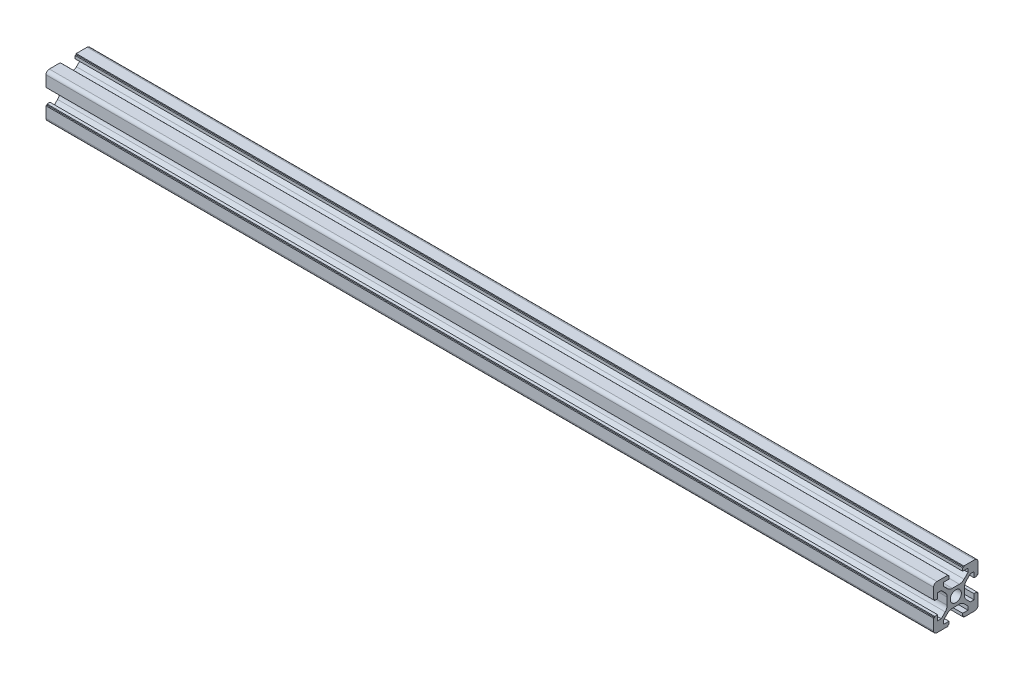
SolidWorks part; units mm, degrees
ref_plane "前视基准面" through (0, 0, 0) normal (0, 0, 1) x (1, 0, 0)
ref_plane "上视基准面" through (0, 0, 0) normal (0, 1, 0) x (1, 0, 0)
ref_plane "右视基准面" through (0, 0, 0) normal (1, 0, 0) x (0, 0, -1)
sketch "草图1" plane through (0, 0, 0) normal (1, 0, 0) x (0, 0, -1)
  line L0 (0, 0) -> (-10, 0) construction
  line L1 (0, 0) -> (0, 10) construction
  line L2 (0, 0) -> (-10, 10) construction
  line L3 (-10, 10) -> (-10, 3.6)
  line L4 (-10, 3.6) -> (-9.531, 3.6)
  line L5 (-9.531, 3.6) -> (-9.531, 3.1)
  line L6 (-9.531, 3.1) -> (-8.2, 3.1)
  line L7 (-8.2, 3.1) -> (-8.2, 5.5)
  line L8 (-8.2, 5.5) -> (-6.5607, 5.5)
  line L9 (-6.5607, 5.5) -> (-3.9, 2.8393)
  line L10 (-3.9, 2.8393) -> (-3.9, 0)
  line L11 (-3.6, 9.531) -> (-3.1, 9.531)
  line L12 (-2.8393, 3.9) -> (0, 3.9)
  line L13 (-5.5, 6.5607) -> (-2.8393, 3.9)
  line L14 (-5.5, 8.2) -> (-5.5, 6.5607)
  line L15 (-3.1, 8.2) -> (-5.5, 8.2)
  line L16 (-3.1, 9.531) -> (-3.1, 8.2)
  line L17 (-3.6, 10) -> (-3.6, 9.531)
  line L18 (-10, 10) -> (-3.6, 10)
  line L19 (0, 0) -> (0, 10) construction
  line L20 (0, 0) -> (10, 0) construction
  line L21 (0, 0) -> (10, 10) construction
  line L22 (10, 10) -> (3.6, 10)
  line L23 (3.6, 10) -> (3.6, 9.531)
  line L24 (3.6, 9.531) -> (3.1, 9.531)
  line L25 (3.1, 9.531) -> (3.1, 8.2)
  line L26 (3.1, 8.2) -> (5.5, 8.2)
  line L27 (5.5, 8.2) -> (5.5, 6.5607)
  line L28 (5.5, 6.5607) -> (2.8393, 3.9)
  line L29 (2.8393, 3.9) -> (0, 3.9)
  line L30 (9.531, 3.6) -> (9.531, 3.1)
  line L31 (3.9, 2.8393) -> (3.9, 0)
  line L32 (6.5607, 5.5) -> (3.9, 2.8393)
  line L33 (8.2, 5.5) -> (6.5607, 5.5)
  line L34 (8.2, 3.1) -> (8.2, 5.5)
  line L35 (9.531, 3.1) -> (8.2, 3.1)
  line L36 (10, 3.6) -> (9.531, 3.6)
  line L37 (10, 10) -> (10, 3.6)
  line L38 (0, 0) -> (10, 0) construction
  line L39 (0, 0) -> (0, -10) construction
  line L40 (0, 0) -> (10, -10) construction
  line L41 (10, -10) -> (10, -3.6)
  line L42 (10, -3.6) -> (9.531, -3.6)
  line L43 (9.531, -3.6) -> (9.531, -3.1)
  line L44 (9.531, -3.1) -> (8.2, -3.1)
  line L45 (8.2, -3.1) -> (8.2, -5.5)
  line L46 (8.2, -5.5) -> (6.5607, -5.5)
  line L47 (6.5607, -5.5) -> (3.9, -2.8393)
  line L48 (3.9, -2.8393) -> (3.9, 0)
  line L49 (3.6, -9.531) -> (3.1, -9.531)
  line L50 (2.8393, -3.9) -> (0, -3.9)
  line L51 (5.5, -6.5607) -> (2.8393, -3.9)
  line L52 (5.5, -8.2) -> (5.5, -6.5607)
  line L53 (3.1, -8.2) -> (5.5, -8.2)
  line L54 (3.1, -9.531) -> (3.1, -8.2)
  line L55 (3.6, -10) -> (3.6, -9.531)
  line L56 (10, -10) -> (3.6, -10)
  line L57 (0, 0) -> (0, -10) construction
  line L58 (0, 0) -> (-10, 0) construction
  line L59 (0, 0) -> (-10, -10) construction
  line L60 (-10, -10) -> (-3.6, -10)
  line L61 (-3.6, -10) -> (-3.6, -9.531)
  line L62 (-3.6, -9.531) -> (-3.1, -9.531)
  line L63 (-3.1, -9.531) -> (-3.1, -8.2)
  line L64 (-3.1, -8.2) -> (-5.5, -8.2)
  line L65 (-5.5, -8.2) -> (-5.5, -6.5607)
  line L66 (-5.5, -6.5607) -> (-2.8393, -3.9)
  line L67 (-2.8393, -3.9) -> (0, -3.9)
  line L68 (-9.531, -3.6) -> (-9.531, -3.1)
  line L69 (-3.9, -2.8393) -> (-3.9, 0)
  line L70 (-6.5607, -5.5) -> (-3.9, -2.8393)
  line L71 (-8.2, -5.5) -> (-6.5607, -5.5)
  line L72 (-8.2, -3.1) -> (-8.2, -5.5)
  line L73 (-9.531, -3.1) -> (-8.2, -3.1)
  line L74 (-10, -3.6) -> (-9.531, -3.6)
  line L75 (-10, -10) -> (-10, -3.6)
  arc A0 (0, 2.5) -> (-2.5, 0) centre (0, 0) ccw
  arc A1 (2.5, 0) -> (0, 2.5) centre (0, 0) ccw
  arc A2 (0, -2.5) -> (2.5, 0) centre (0, 0) ccw
  arc A3 (-2.5, 0) -> (0, -2.5) centre (0, 0) ccw
  point P89 (0, 0)
  dimension "D3" = 5
  dimension "D1" = 10
  dimension "D2" = 10
  dimension "D4" = 10
  dimension "D5" = 1.8
  dimension "D6" = 5.5
  dimension "D7" = 3.1
  dimension "D8" = 3.6
  dimension "D9" = 6.1
  dimension "D10" = 0.75
  dimension "D11" = 4
extrude "凸台-拉伸1" add sketch "草图1" along normal blind 400
fillet "圆角1" radius 1.5 4 edges at (200, -10, -10) (200, -10, 10) (200, 10, -10) (200, 10, 10)
fillet "圆角2" radius 3 8 edges at (200, -3.9, 2.8393) (200, -3.9, -2.8393) (200, -2.8393, -3.9) (200, 2.8393, -3.9) (200, 2.8393, 3.9) (200, -2.8393, 3.9) (200, 3.9, 2.8393) (200, 3.9, -2.8393)
